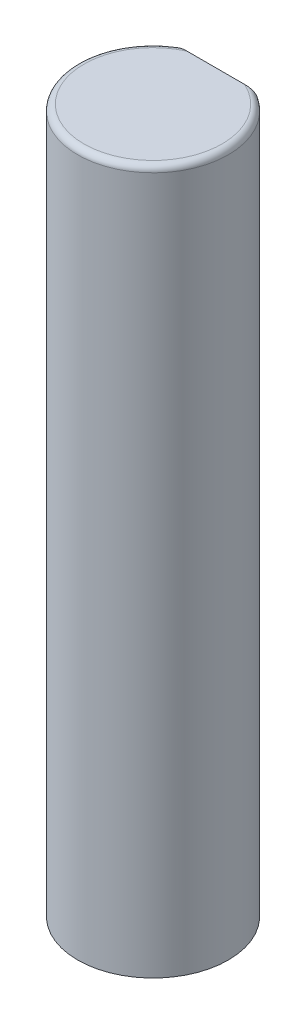
SolidWorks part; units mm, degrees
material "Plain Carbon Steel"
ref_plane "Front Plane" through (0, 0, 0) normal (0, 0, 1) x (1, 0, 0)
ref_plane "Top Plane" through (0, 0, 0) normal (0, 1, 0) x (1, 0, 0)
ref_plane "Right Plane" through (0, 0, 0) normal (1, 0, 0) x (0, 0, -1)
sketch "Sketch1" plane through (0, 0, 0) normal (0, 1, 0) x (1, 0, 0)
  circle A0 centre (0, 0) radius 3
  dimension "D1" = 6
extrude "Boss-Extrude1" add sketch "Sketch1" along normal blind 28
sketch "Sketch2" plane through (0, 28, 0) normal (0, 1, 0) x (1, 0, 0)
  line L0 (0, 0) -> (0, 3) construction
  line L2 (3, 2.5) -> (-3, 2.5)
  line L3 (3, 2.5) -> (3, 3.5)
  line L4 (3, 3.5) -> (-3, 3.5)
  line L5 (-3, 2.5) -> (-3, 3.5)
  line L6 (3, 2.5) -> (-3, 3.5) construction
  line L7 (3, 3.5) -> (-3, 2.5) construction
  circle A0 centre (0, 0) radius 3 construction
  point P6 (0, 3)
  dimension "D1" = 1
  dimension "D2" = 6
extrude "Cut-Extrude1" cut sketch "Sketch2" against normal blind 12
fillet "Fillet1" radius 0.25 1 edges at (0, 28, 3)
